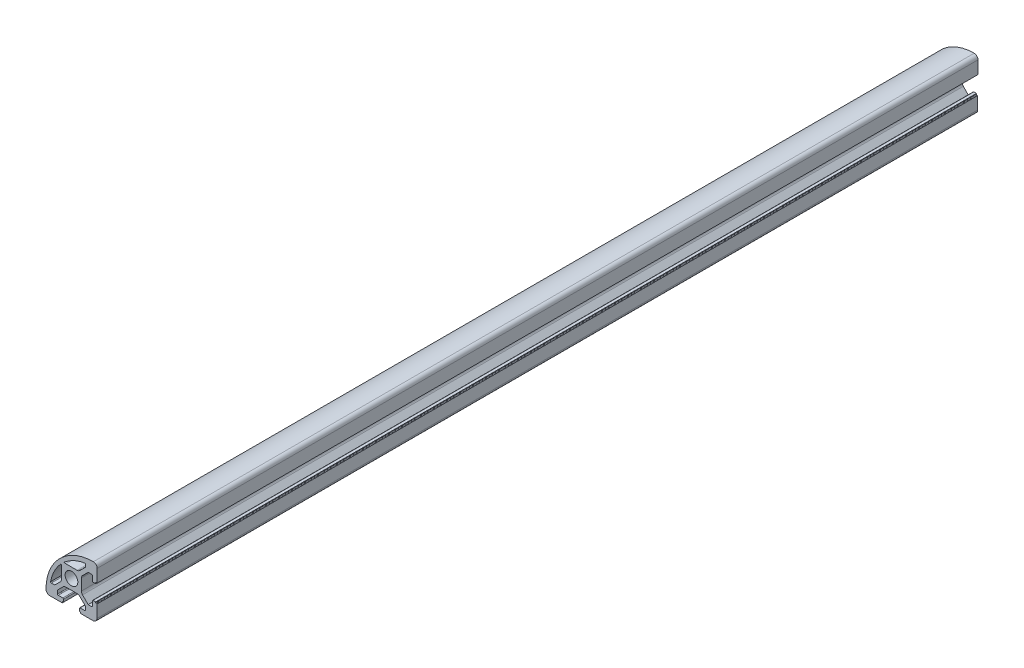
SolidWorks part; units mm, degrees
ref_plane "前视基准面" through (0, 0, 0) normal (0, 0, 1) x (1, 0, 0)
ref_plane "上视基准面" through (0, 0, 0) normal (0, 1, 0) x (1, 0, 0)
ref_plane "右视基准面" through (0, 0, 0) normal (1, 0, 0) x (0, 0, -1)
sketch "草图1" plane through (0, 0, 0) normal (0, 0, 1) x (1, 0, 0)
  line L0 (4.216, 3.1292) -> (6.4367, 5.3498)
  line L1 (6.4367, 5.3498) -> (7.7767, 5.3498)
  line L2 (8.0767, 5.0498) -> (8.0767, 3.2498)
  line L3 (8.3767, 2.9498) -> (9.3767, 2.9498)
  line L4 (9.3767, 2.9498) -> (9.3767, 3.2498)
  line L5 (9.5767, 3.4498) -> (9.9921, 3.4498)
  line L6 (9.9921, 3.4498) -> (9.9921, 8.4652)
  line L12 (5.3767, 7.8649) -> (5.3767, 6.5249)
  line L13 (5.3767, 6.5249) -> (3.156, 4.3042)
  line L14 (2.0953, 3.8649) -> (-2.342, 3.8649)
  line L29 (-4.0233, 2.1836) -> (-4.0233, -2.2538)
  line L30 (-4.4627, -3.3144) -> (-6.6833, -5.5351)
  line L31 (-6.6833, -5.5351) -> (-8.0233, -5.5351)
  line L37 (-8.6233, -10.1502) -> (-3.7233, -10.1502)
  line L38 (-3.7233, -10.1502) -> (-3.7233, -9.8502)
  line L39 (-3.5233, -9.6502) -> (-3.2233, -9.6502)
  line L40 (-3.2233, -9.6502) -> (-3.2233, -8.6502)
  line L41 (-3.5233, -8.3502) -> (-5.3233, -8.3502)
  line L42 (-5.6233, -8.0502) -> (-5.6233, -6.7102)
  line L43 (-5.6233, -6.7102) -> (-3.4027, -4.4895)
  line L44 (-2.342, -4.0502) -> (2.0953, -4.0502)
  line L45 (3.156, -4.4895) -> (5.3767, -6.7102)
  line L46 (5.3767, -6.7102) -> (5.3767, -8.0502)
  line L47 (5.0767, -8.3502) -> (3.2767, -8.3502)
  line L48 (2.9767, -8.6502) -> (2.9767, -9.6502)
  line L49 (2.9767, -9.6502) -> (3.2767, -9.6502)
  line L50 (3.4767, -9.8502) -> (3.4767, -10.1502)
  line L51 (3.4767, -10.1502) -> (8.3767, -10.1502)
  line L52 (9.8767, -8.6502) -> (9.8767, -3.7502)
  line L53 (9.8767, -3.7502) -> (9.5767, -3.7502)
  line L54 (9.3767, -3.5502) -> (9.3767, -3.2502)
  line L55 (9.3767, -3.2502) -> (8.3767, -3.2502)
  line L56 (8.0767, -3.5502) -> (8.0767, -5.3502)
  line L57 (7.7767, -5.6502) -> (6.4367, -5.6502)
  line L58 (6.4367, -5.6502) -> (4.216, -3.4295)
  line L59 (3.7767, -2.3689) -> (3.7767, 2.0685)
  circle A0 centre (-0.1233, -0.0351) radius 2.5
  arc A1 (8.0767, 5.0498) -> (7.7767, 5.3498) centre (7.7767, 5.0498) ccw
  arc A2 (8.0767, 3.2498) -> (8.3767, 2.9498) centre (8.3767, 3.2498) ccw
  arc A3 (9.5767, 3.4498) -> (9.3767, 3.2498) centre (9.5767, 3.2498) ccw
  arc A4 (9.9921, 8.4652) -> (8.4921, 9.9652) centre (8.4921, 8.4652) ccw
  arc A8 (2.0953, 3.8649) -> (3.156, 4.3042) centre (2.0953, 5.3649) ccw
  arc A9 (-3.0267, 4.0303) -> (-2.342, 3.8649) centre (-2.342, 5.3649) ccw
  arc A10 (-3.0267, 4.0303) -> (5.3767, 7.8649) centre (7.6364, -8.2121) cw
  arc A17 (-4.0233, 2.1836) -> (-4.2034, 2.8962) centre (-5.5233, 2.1836) ccw
  arc A18 (-4.4627, -3.3144) -> (-4.0233, -2.2538) centre (-5.5233, -2.2538) ccw
  arc A19 (-8.3233, -5.2351) -> (-8.0233, -5.5351) centre (-8.0233, -5.2351) ccw
  arc A22 (-10.1233, -8.6502) -> (-8.6233, -10.1502) centre (-8.6233, -8.6502) ccw
  arc A23 (-3.5233, -9.6502) -> (-3.7233, -9.8502) centre (-3.5233, -9.8502) ccw
  arc A24 (-3.2233, -8.6502) -> (-3.5233, -8.3502) centre (-3.5233, -8.6502) ccw
  arc A25 (-5.6233, -8.0502) -> (-5.3233, -8.3502) centre (-5.3233, -8.0502) ccw
  arc A26 (-2.342, -4.0502) -> (-3.4027, -4.4895) centre (-2.342, -5.5502) ccw
  arc A27 (3.156, -4.4895) -> (2.0953, -4.0502) centre (2.0953, -5.5502) ccw
  arc A28 (5.0767, -8.3502) -> (5.3767, -8.0502) centre (5.0767, -8.0502) ccw
  arc A29 (3.2767, -8.3502) -> (2.9767, -8.6502) centre (3.2767, -8.6502) ccw
  arc A30 (3.4767, -9.8502) -> (3.2767, -9.6502) centre (3.2767, -9.8502) ccw
  arc A31 (8.3767, -10.1502) -> (9.8767, -8.6502) centre (8.3767, -8.6502) ccw
  arc A32 (9.3767, -3.5502) -> (9.5767, -3.7502) centre (9.5767, -3.5502) ccw
  arc A33 (8.3767, -3.2502) -> (8.0767, -3.5502) centre (8.3767, -3.5502) ccw
  arc A34 (7.7767, -5.6502) -> (8.0767, -5.3502) centre (7.7767, -5.3502) ccw
  arc A35 (3.7767, -2.3689) -> (4.216, -3.4295) centre (5.2767, -2.3689) ccw
  arc A36 (4.216, 3.1292) -> (3.7767, 2.0685) centre (5.2767, 2.0685) ccw
  arc A37 (8.4921, 9.9652) -> (-10.1233, -8.6502) centre (8.4921, -8.6502) ccw
  arc A38 (-8.3233, -5.2351) -> (-4.2034, 2.8962) centre (7.6364, -8.2121) cw
extrude "凸台-拉伸1" add sketch "草图1" along normal blind 346
